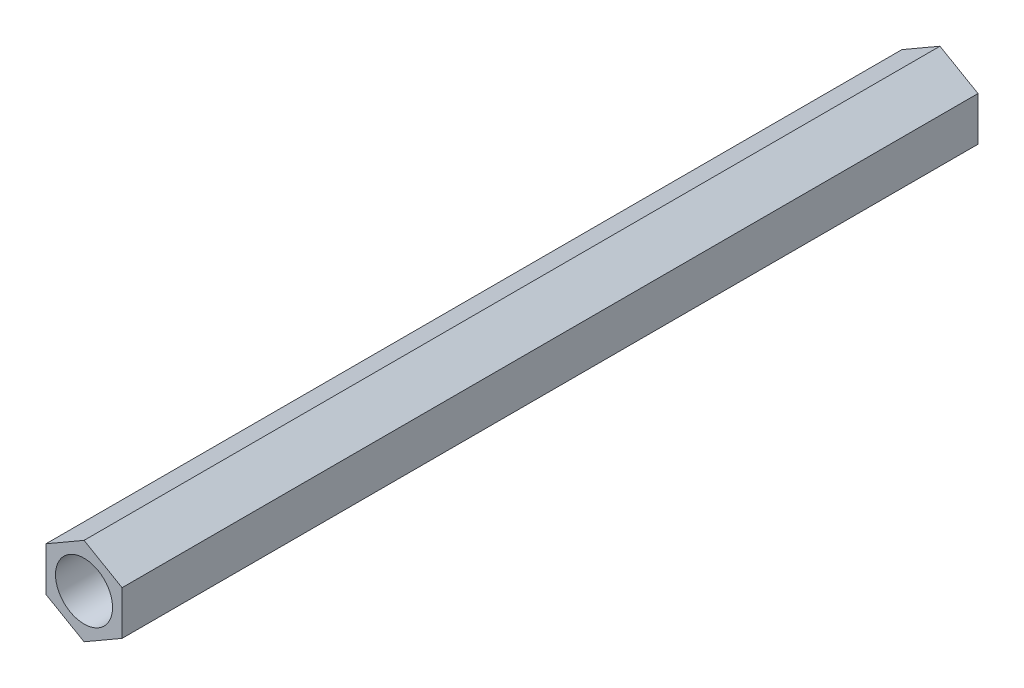
SolidWorks part; units mm, degrees
material "1060 合金"
ref_plane "前视基准面" through (0, 0, 0) normal (0, 0, 1) x (1, 0, 0)
ref_plane "上视基准面" through (0, 0, 0) normal (0, 1, 0) x (1, 0, 0)
ref_plane "右视基准面" through (0, 0, 0) normal (1, 0, 0) x (0, 0, -1)
other "Configuration Table"
sketch "草图1" plane through (0, 0, 0) normal (0, 0, 1) x (1, 0, 0)
  circle A0 centre (0, 0) radius 3
  circle A1 centre (0, 0) radius 4
  dimension "D1" = 6
  dimension "D2" = 8
extrude "凸台-拉伸1" add sketch "草图1" along normal blind 90
sketch "草图2" plane through (0, 0, 90) normal (0, 0, 1) x (1, 0, 0)
  line L0 (0, 4.6188) -> (0, 0) construction
  line L1 (4, 2.3094) -> (0, 4.6188)
  line L2 (0, 4.6188) -> (-4, 2.3094)
  line L3 (-4, 2.3094) -> (-4, -2.3094)
  line L4 (-4, -2.3094) -> (0, -4.6188)
  line L5 (0, -4.6188) -> (4, -2.3094)
  line L6 (4, -2.3094) -> (4, 2.3094)
  circle A0 centre (0, 0) radius 4 construction
  circle A1 centre (0, 0) radius 4 construction
  circle A2 centre (0, 0) radius 3 construction
  circle A3 centre (0, 0) radius 3
extrude "凸台-拉伸2" add sketch "草图2" against normal up to surface (90 mm away) up to face at (4, 0, 0)
